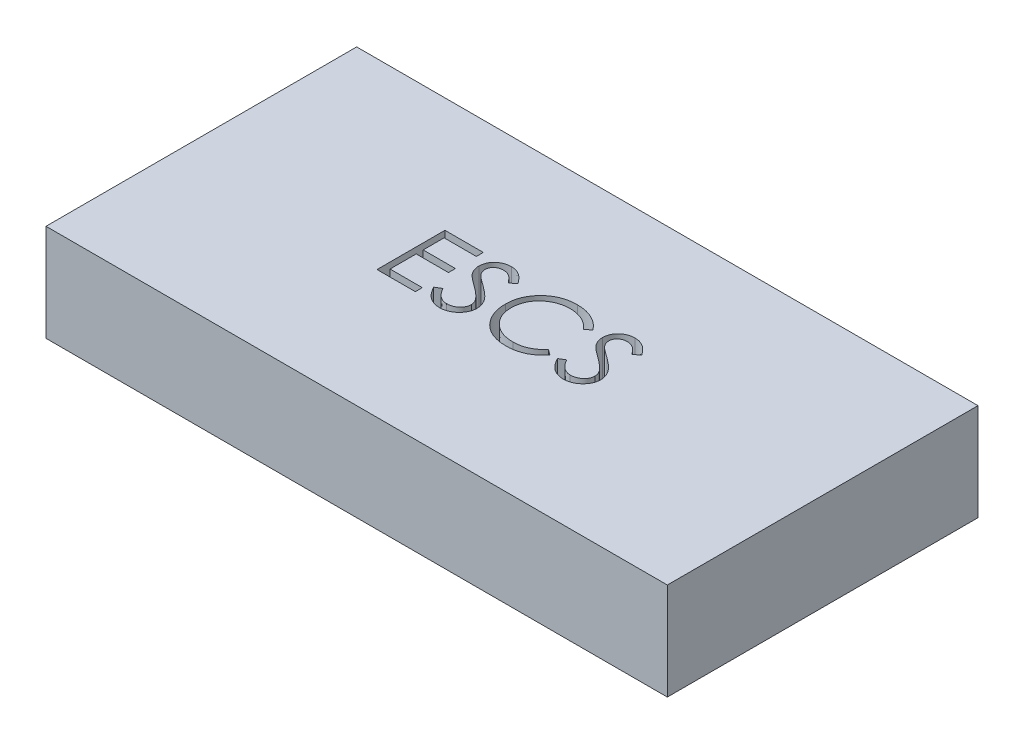
SolidWorks part; units mm, degrees
ref_plane "Front Plane" through (0, 0, 0) normal (0, 0, 1) x (1, 0, 0)
ref_plane "Top Plane" through (0, 0, 0) normal (0, 1, 0) x (1, 0, 0)
ref_plane "Right Plane" through (0, 0, 0) normal (1, 0, 0) x (0, 0, -1)
sketch "Sketch1" plane through (0, 0, 0) normal (0, 1, 0) x (1, 0, 0)
  line L1 (-17.417, 13.4317) -> (14.583, 13.4317)
  line L2 (-17.417, 13.4317) -> (-17.417, -2.5683)
  line L3 (-17.417, -2.5683) -> (14.583, -2.5683)
  line L4 (14.583, 13.4317) -> (14.583, -2.5683)
  dimension "D1" = 32
  dimension "D2" = 16
extrude "Boss-Extrude1" add sketch "Sketch1" along normal blind 5
sketch "Sketch3" plane through (0, 5, 0) normal (0, 1, 0) x (1, 0, 0)
  text T0 "ESCS"
extrude "Cut-Extrude3" cut sketch "Sketch3" against normal blind 2
